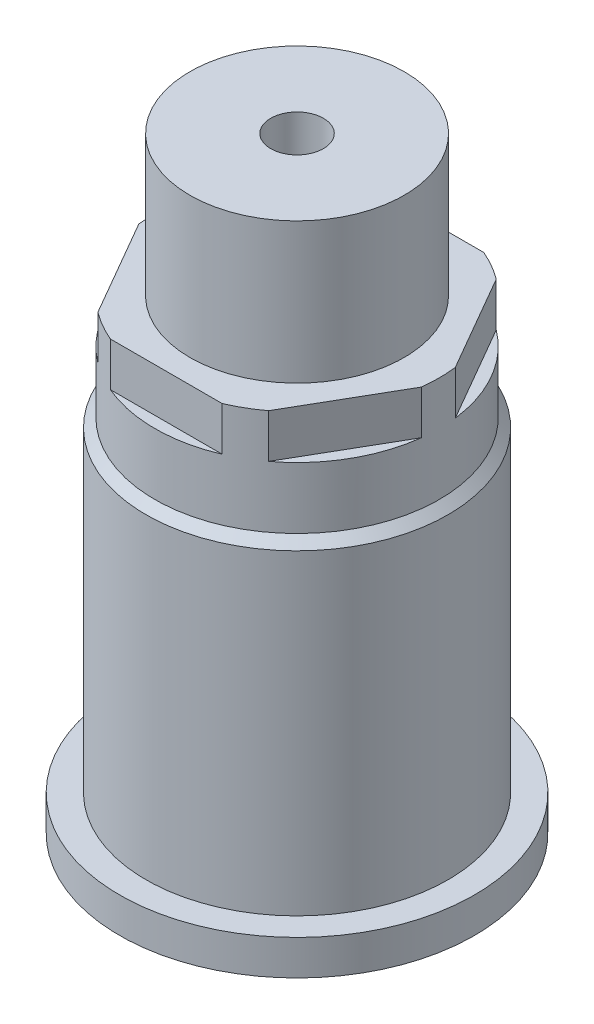
SolidWorks part; units mm, degrees
ref_plane "Front Plane" through (0, 0, 0) normal (0, 0, 1) x (1, 0, 0)
ref_plane "Top Plane" through (0, 0, 0) normal (0, 1, 0) x (1, 0, 0)
ref_plane "Right Plane" through (0, 0, 0) normal (1, 0, 0) x (0, 0, -1)
sketch "Sketch1" plane through (0, 0, 0) normal (0, 0, 1) x (1, 0, 0)
  line L0 (0, 0) -> (11.557, 0)
  line L1 (11.557, 0) -> (11.557, -1.27)
  line L2 (11.557, -1.27) -> (12.827, -1.27)
  line L3 (12.827, -1.27) -> (12.827, 1.27)
  line L4 (12.827, 1.27) -> (10.922, 1.27)
  line L5 (10.922, 1.27) -> (10.922, 24.13)
  line L6 (10.922, 24.13) -> (10.287, 24.765)
  line L7 (10.287, 24.765) -> (10.287, 32.385)
  line L8 (10.287, 32.385) -> (0, 32.385) construction
  line L9 (0, 0) -> (0, 32.385)
  line L10 (7.747, 32.385) -> (7.747, 42.545)
  line L11 (0, 32.385) -> (0, 42.545)
  line L12 (7.747, 42.545) -> (0, 42.545)
  line L13 (7.747, 32.385) -> (10.287, 32.385)
  dimension "D2" = 1.27
  dimension "D3" = 1.27
  dimension "D4" = 2.54
  dimension "D5" = 1.905
  dimension "D6" = 22.86
  dimension "D7" = 135
  dimension "D8" = 7.62
  dimension "D9" = 0.635
  dimension "D10" = 10.16
  dimension "D11" = 2.54
  dimension "D12" = 10.922
revolve "Revolve1" add sketch "Sketch1" angle 360 about L9
sketch "Sketch2" plane through (0, 32.385, 0) normal (0, 1, 0) x (1, 0, 0)
  line L0 (-10.922, 0) -> (10.922, 0) construction
  line L1 (-10.922, 0) -> (-5.461, -9.4587)
  line L2 (-5.461, -9.4587) -> (5.461, -9.4587)
  line L3 (5.461, -9.4587) -> (10.922, 0)
  line L4 (10.922, 0) -> (5.461, 9.4587)
  line L5 (5.461, 9.4587) -> (-5.461, 9.4587)
  line L6 (-5.461, 9.4587) -> (-10.922, 0)
  circle A0 centre (0, 0) radius 9.4587 construction
  circle A1 centre (0, 0) radius 12.827
  circle A2 centre (0, 0) radius 12.827 construction
  dimension "D1" = 10.922
extrude "Cut-Extrude1" cut sketch "Sketch2" against normal blind 3.175
sketch "Sketch3" plane through (0, 42.545, 0) normal (0, 1, 0) x (1, 0, 0)
  circle A0 centre (0, 0) radius 1.905
  dimension "D1" = 3.81
extrude "Cut-Extrude2" cut sketch "Sketch3" against normal blind 33.02 and the other way through all
